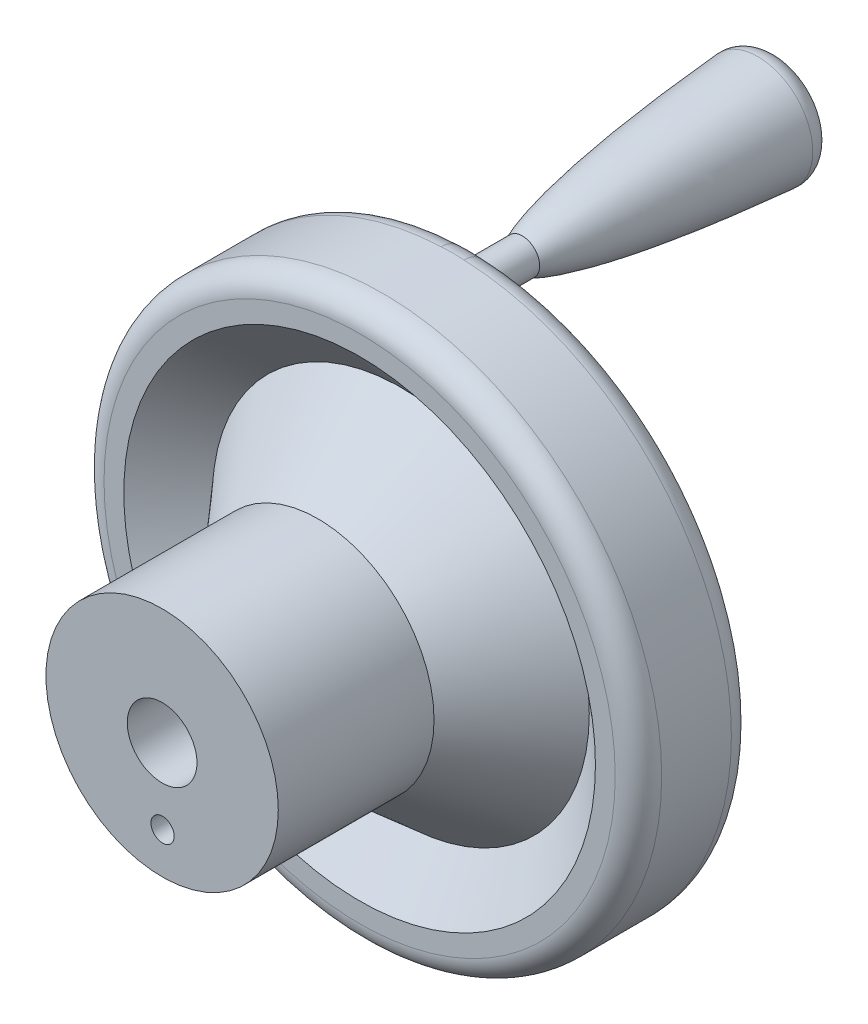
SolidWorks part; units mm, degrees
ref_plane "Front Plane" through (0, 0, 0) normal (0, 0, 1) x (1, 0, 0)
ref_plane "Top Plane" through (0, 0, 0) normal (0, 1, 0) x (1, 0, 0)
ref_plane "Right Plane" through (0, 0, 0) normal (1, 0, 0) x (0, 0, -1)
sketch "Sketch2" plane through (0, 0, 0) normal (1, 0, 0) x (0, 0, -1)
  line L0 (21.2808, 31.75) -> (32.6249, 41.6177)
  line L1 (0, 0) -> (21.2808, 0)
  line L2 (0, 0) -> (0, 13.335)
  line L3 (0, 31.75) -> (21.2808, 31.75)
  line L4 (26.9875, 3.4522) -> (26.9875, 28.2978)
  line L5 (26.9875, -22.225) -> (42.8625, -22.225)
  line L6 (26.9875, -22.225) -> (26.9875, -16.3486)
  line L7 (26.9875, 53.975) -> (42.8625, 53.975)
  line L8 (42.8625, -22.225) -> (42.8625, 53.975)
  line L9 (26.9875, 28.2978) -> (42.8625, 42.1066)
  line L10 (26.9875, 48.0986) -> (26.9875, 53.975)
  line L11 (32.6249, 41.6177) -> (26.9875, 48.0986)
  line L12 (0, 15.875) -> (106.1386, 15.875) construction
  line L13 (26.9875, -16.3486) -> (26.9875, -22.225)
  line L14 (32.6249, -9.8677) -> (26.9875, -16.3486)
  line L15 (26.9875, 3.4522) -> (42.8625, -10.3566)
  line L16 (21.2808, 0) -> (32.6249, -9.8677)
  line L17 (26.9875, 3.4522) -> (26.9875, 28.2978)
  line L18 (0, 18.415) -> (0, 31.75)
  line L19 (0, 13.335) -> (12.7, 13.335)
  line L21 (0, 18.415) -> (12.7, 18.415)
  line L22 (12.7, 13.335) -> (12.7, 18.415)
  dimension "D1" = 12.7
  dimension "D2" = 2.54
  dimension "D3" = 5.08
  dimension "D4" = 31.75
  dimension "D5" = 76.2
  dimension "D6" = 42.8625
  dimension "D7" = 15.875
  dimension "D8" = 6.35
revolve "Revolve1" add sketch "Sketch2" angle 360 about L12
sketch "Sketch3" plane through (0, 0, -42.8625) normal (0, 0, -1) x (-1, 0, 0)
  circle A0 centre (0, 48.8675) radius 2.3812
  dimension "D1" = 4.7625
extrude "Boss-Extrude1" add sketch "Sketch3" along normal blind 6.35
sketch "Sketch4" plane through (0, 0, 0) normal (1, 0, 0) x (0, 0, -1)
  line L0 (49.2125, 51.2488) -> (49.2125, 46.4863)
  line L1 (84.1375, 56.558) -> (84.1375, 41.1771)
  line L2 (49.2125, 48.8675) -> (98.7786, 48.8675) construction
  line L3 (42.8625, -22.225) -> (42.8625, 53.975) construction
  ellipse E0 centre (122.2682, 48.8675) end of major axis (46.4466, 48.8675) minor radius 8.8974 (49.2125, 46.4863) -> (84.1375, 41.1771) ccw
  ellipse E1 centre (122.2682, 48.8675) end of major axis (46.4466, 48.8675) minor radius 8.8974 (84.1375, 56.558) -> (49.2125, 51.2488) ccw
  dimension "D1" = 41.275
revolve "Revolve2" add sketch "Sketch4" angle 360 about L2
fillet "Fillet1" radius 2.54 1 edges at (7.6904, 48.8675, -84.1375)
fillet "Fillet2" [suppressed] radius 1.27
fillet "Fillet3" radius 3.175 3 edges at (38.1, 15.875, -26.9875) (38.1, 15.875, -42.8625) (12.4228, 15.875, -26.9875)
sketch "Sketch5" plane through (0, 0, 0) normal (0, 0, 1) x (1, 0, 0)
  circle A0 centre (0, 15.875) radius 4.7625
  dimension "D1" = 9.525
extrude "screw hole Cut-Extrude2" cut sketch "Sketch5" against normal through all
hole_wizard "1/8 (0.125) Diameter Hole1" positions "Sketch8" profile "Sketch9" hole size "1/8" standard "ANSI Inch"
sketch "Sketch8" plane through (-4.3421, -24.3909, 0) normal (0, 0, 1) x (1, 0, 0)
  line L0 (4.3421, 35.5034) -> (4.4691, 24.5179) construction
  point P0 (4.4056, 30.0107)
sketch "Sketch9" plane through (0.0635, 5.6197, 0) normal (1, 0, 0) x (0, -1, 0)
  line L0 (0, 0) -> (0, 12.7)
  line L1 (0, 12.7) -> (1.5875, 12.7)
  line L2 (1.5875, 12.7) -> (1.5875, 0)
  line L3 (1.5875, 0) -> (0, 0)
  line L4 (0, -6.35) -> (0, 107.95) construction
  dimension "Thru Hole Dia." = 3.175
  dimension "Thru Hole Depth" = 12.7
equation "\"dovetail-angle\"= 55"
equation "\"dovetail-stock-width\"= 5"
equation "\"dovetail-stock-height\"= 1.25"
equation "\"dovetail-depth\"= 0.5 * \"dovetail-stock-height\""
equation "\"dovetail-throat-width\"= \"dovetail-stock-width\" - (2 * \"dovetail-depth\")"
equation "\"delta-x\"= 6"
equation "\"delta-y\"= 3"
equation "\"gib-thickness\"= 0.25"
equation "\"x-slide-length\"= \"dovetail-stock-width\" + \"delta-x\""
equation "\"y-slide-length\"= \"dovetail-stock-width\" + \"delta-y\""
equation "\"dog-point-diam\"= .149"
equation "\"dog-point-length\"= .067"
equation "\"dovetail-double-height\"= 2 * \"dovetail-depth\" + 0.5"
equation "\"acme-major-diam\"= .5"
equation "\"acme-pitch-diam\"= 0.45"
equation "\"acme-minor-diam\"= 0.4"
equation "\"acme-nut-od\"= 1.47"
equation "\"acme-nut-length\"= 1"
equation "\"acme-nut-trim-height\"= .75"
equation "\"screw-bearing-od\"= 0.5"
equation "\"screw-bearing-length\"= .25"
equation "\"screw-bearing-id\"= .375"
equation "\"end-plate-thickness\"= \"screw-bearing-length\""
equation "\"screw-add-length\"= 2 * \"end-plate-thickness\" + 1 + 0.5"
equation "\"x-screw-length\"= \"x-slide-length\" + \"screw-add-length\""
equation "\"y-screw-length\"= \"y-slide-length\" + \"screw-add-length\""
equation "\"acme-nut-mount-hole-space-horz\"= 0.82"
equation "\"acme-nut-mount-hole-space-vert\"= 0.5 * \"acme-nut-length\""
equation "\"vise-hole-center-dist\"= 6.75"
equation "\"wiper_plate_clearance\"= .03"
equation "\"dial-width\"= 0.5"
equation "\"D1@Sketch5\"=\"screw-bearing-id\""
